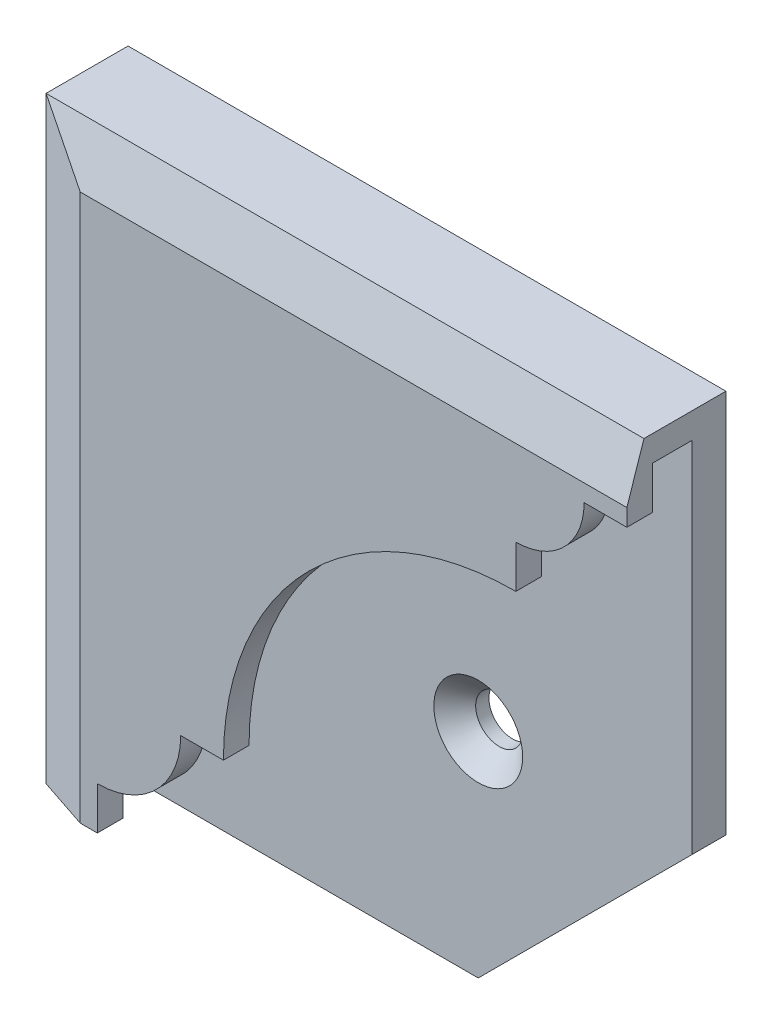
SolidWorks part; units mm, degrees
ref_plane "Plan de face" through (0, 0, 0) normal (0, 0, 1) x (1, 0, 0)
ref_plane "Plan de dessus" through (0, 0, 0) normal (0, 1, 0) x (1, 0, 0)
ref_plane "Plan de droite" through (0, 0, 0) normal (1, 0, 0) x (0, 0, -1)
sketch "Esquisse1" plane through (0, 0, 0) normal (0, 0, 1) x (1, 0, 0)
  line L1 (-35, -35) -> (35, -35)
  line L2 (-35, -35) -> (-35, 35)
  line L3 (-35, 35) -> (35, 35)
  line L4 (35, -35) -> (35, 35)
  line L5 (-35, -35) -> (35, 35) construction
  line L6 (-35, 35) -> (35, -35) construction
  point P0 (0, 0)
  dimension "D1" = 70
extrude "Boss.-Extru.1" add sketch "Esquisse1" along normal blind 4
sketch "Esquisse2" plane through (0, 0, 4) normal (0, 0, 1) x (1, 0, 0)
  line L0 (-35, 35) -> (-35, -35) construction
  line L1 (35, 35) -> (-35, 35) construction
  line L2 (-35, 35) -> (-35, -35)
  line L3 (35, 35) -> (-35, 35)
  line L4 (-35, -35) -> (-32, -35)
  line L6 (-35, -35) -> (35, -35) construction
  line L7 (-32, -35) -> (-32, 32)
  line L8 (-32, 32) -> (35, 32)
  line L9 (35, -35) -> (35, 35) construction
  line L11 (35, 32) -> (35, 35)
  dimension "D1" = 3
extrude "Boss.-Extru.2" add sketch "Esquisse2" along normal blind 4.6
sketch "Esquisse3" plane through (0, 0, 8.6) normal (0, 0, 1) x (1, 0, 0)
  line L0 (35, 35) -> (-35, 35) construction
  line L1 (-35, 35) -> (-35, -35) construction
  line L2 (35, 35) -> (-35, 35)
  line L3 (-35, 35) -> (-35, -35)
  line L4 (35, 35) -> (35, 27)
  line L5 (35, -35) -> (35, 32) construction
  line L6 (35, 27) -> (30, 27)
  line L7 (22, 19) -> (22, 14)
  line L8 (-12.235, -20.235) -> (-17.235, -20.235)
  line L9 (-27, -30) -> (-27, -35)
  line L10 (-32, -35) -> (35, -35) construction
  line L11 (-27, -35) -> (-35, -35)
  arc A0 (30, 27) -> (22, 19) centre (22, 27) cw
  arc A1 (22, 14) -> (-12.235, -20.235) centre (22, -20.235) ccw
  arc A2 (-17.235, -20.235) -> (-27, -30) centre (-27, -20.235) cw
  dimension "D3" = 8
  dimension "D1" = 8
  dimension "D2" = 5
extrude "Boss.-Extru.3" add sketch "Esquisse3" along normal blind 3
chamfer "Chanfrein1" distance 2 distance2 6 2 edges at (-35, 0, 11.6) (0, 35, 11.6)
chamfer "Chanfrein2" distance 25 angle 45 1 edges at (35, -35, 2)
hole_wizard "Fraisage pour vis à tête fraisée M51" positions "Esquisse5" profile "Esquisse4" countersink size "M5" standard "Ansi Metric" end condition up to next
sketch "Esquisse5" plane through (0, 0, 4) normal (0, 0, 1) x (1, 0, 0)
  line L0 (35, -10) -> (35, 32) construction
  line L1 (-32, -35) -> (10, -35) construction
  point P0 (10, -10)
  dimension "D1" = 25
  dimension "D2" = 25
sketch "Esquisse4" plane through (10, -10, 4) normal (1, 0, 0) x (0, -1, 0)
  line L0 (0, 0) -> (0, 4)
  line L1 (0, 4) -> (2.75, 4)
  line L2 (2.75, 4) -> (2.75, 2.45)
  line L3 (2.75, 2.45) -> (5.2, 0)
  line L5 (5.2, 0) -> (0, 0)
  line L6 (-2.75, 2.45) -> (-5.2, 0) construction
  line L11 (0, -6.35) -> (0, 107.95) construction
  dimension "Diamètre du perçage jusqu'au prochain" = 5.5
  dimension "Profondeur du perçage jusqu'au prochain" = 4
  dimension "Diamètre du fraisage entrant" = 10.4
  dimension "Angle du fraisage entrant" = 90
